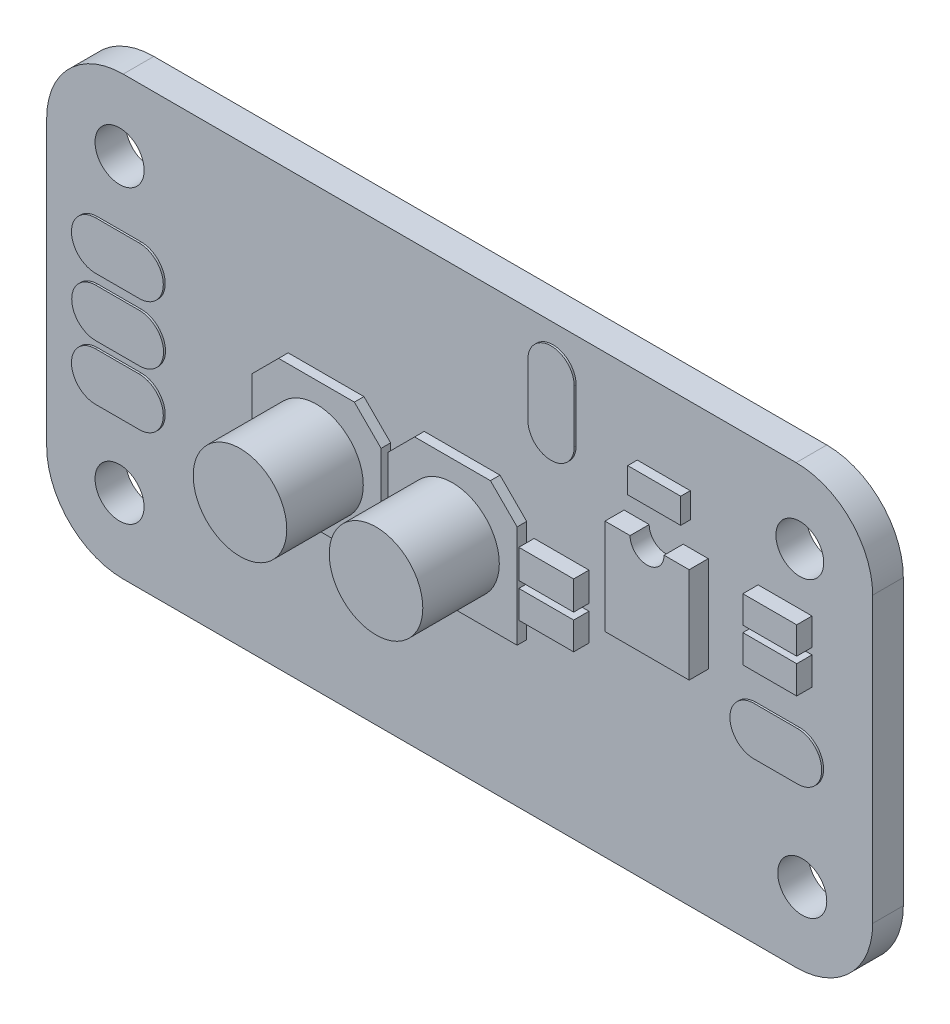
SolidWorks part; units mm, degrees
ref_plane "前视基准面" through (0, 0, 0) normal (0, 0, 1) x (1, 0, 0)
ref_plane "上视基准面" through (0, 0, 0) normal (0, 1, 0) x (1, 0, 0)
ref_plane "右视基准面" through (0, 0, 0) normal (1, 0, 0) x (0, 0, -1)
sketch "Model" plane through (0, 0, 0) normal (0, 0, 1) x (1, 0, 0)
  line L0 (38.097, 21.59) -> (2.5415, 21.59)
  line L1 (41.91, 2.543) -> (41.91, 17.9212)
  line L2 (2.54, -1.27) -> (38.2312, -1.27)
  line L3 (-1.2685, 17.7785) -> (-1.2685, 2.54)
  line L4 (22.225, 14.732) -> (26.67, 14.732)
  line L5 (26.67, 14.732) -> (27.051, 15.113)
  line L6 (27.051, 15.113) -> (27.94, 16.002)
  line L7 (27.94, 16.002) -> (27.94, 20.955)
  line L8 (22.225, 20.955) -> (22.225, 14.732)
  line L9 (22.225, 14.732) -> (23.876, 13.081)
  line L10 (23.876, 13.081) -> (23.876, 6.223)
  line L11 (23.876, 6.223) -> (25.019, 5.08)
  line L12 (25.019, 5.08) -> (39.624, 5.08)
  line L13 (39.624, 5.08) -> (41.021, 6.477)
  line L14 (41.021, 6.477) -> (41.021, 17.145)
  line L15 (28.956, 20.955) -> (22.225, 20.955)
  line L16 (37.211, 20.955) -> (28.956, 20.955)
  line L17 (33.8201, 11.811) -> (34.798, 11.811)
  line L18 (34.798, 11.811) -> (36.957, 9.652)
  line L19 (36.957, 9.652) -> (36.957, 8.509)
  line L20 (28.448, 11.811) -> (29.337, 11.811)
  line L21 (29.337, 11.811) -> (30.988, 10.16)
  line L22 (30.988, 10.16) -> (30.988, 8.509)
  line L23 (30.988, 8.509) -> (31.877, 7.62)
  line L24 (31.877, 7.62) -> (33.401, 7.62)
  line L25 (33.401, 7.62) -> (35.687, 5.334)
  line L26 (35.687, 5.334) -> (39.497, 5.334)
  line L27 (39.497, 5.334) -> (40.132, 5.969)
  line L28 (40.132, 5.969) -> (40.132, 9.398)
  line L29 (40.132, 9.398) -> (38.039, 11.491)
  line L30 (38.039, 11.491) -> (38.039, 12.573)
  line L31 (2.54, 13.208) -> (2.667, 13.208)
  line L32 (2.667, 13.208) -> (6.35, 16.891)
  line L33 (6.35, 16.891) -> (11.049, 16.891)
  line L34 (11.049, 16.891) -> (13.335, 14.605)
  line L35 (13.335, 14.605) -> (13.335, 13.335)
  line L36 (13.335, 7.236) -> (15.618, 7.236)
  line L37 (15.618, 7.236) -> (16.764, 8.382)
  line L38 (16.764, 8.382) -> (16.764, 10.922)
  line L39 (16.764, 10.922) -> (18.415, 12.573)
  line L40 (18.415, 12.573) -> (18.418, 12.576)
  line L41 (18.418, 12.576) -> (20.447, 12.576)
  line L42 (2.54, 7.112) -> (3.175, 7.112)
  line L43 (3.175, 7.112) -> (6.604, 3.683)
  line L44 (6.604, 3.683) -> (17.018, 3.683)
  line L45 (17.018, 3.683) -> (20.447, 7.112)
  line L46 (20.447, 7.112) -> (20.447, 7.236)
  line L47 (3.683, 10.16) -> (4.699, 10.16)
  line L48 (4.699, 10.16) -> (7.623, 7.236)
  line L49 (7.623, 7.236) -> (13.335, 7.236)
  line L50 (1.397, 10.16) -> (3.683, 10.16)
  line L51 (31.7414, 16.891) -> (31.7414, 12.7086)
  line L52 (31.7414, 12.7086) -> (32.639, 11.811)
  line L53 (32.639, 11.811) -> (33.8201, 11.811)
  line L54 (28.4099, 13.081) -> (29.464, 13.081)
  line L55 (29.464, 13.081) -> (30.2346, 13.8516)
  line L56 (30.2346, 13.8516) -> (30.2346, 16.891)
  line L57 (20.447, 12.576) -> (21.46, 12.576)
  line L58 (21.46, 12.576) -> (23.495, 10.541)
  line L59 (23.495, 10.541) -> (24.954, 10.541)
  line L60 (24.954, 8.763) -> (24.954, 10.541)
  line L61 (26.354, 8.763) -> (26.354, 10.541)
  line L62 (26.354, 10.541) -> (28.4099, 10.541)
  line L63 (20.447, 7.236) -> (22.736, 7.236)
  line L64 (22.736, 7.236) -> (23.495, 6.477)
  line L65 (23.495, 6.477) -> (25.527, 6.477)
  line L66 (25.527, 6.477) -> (26.354, 7.304)
  line L67 (26.354, 7.304) -> (26.354, 8.763)
  line L68 (36.638, 14.351) -> (36.576, 14.289)
  line L69 (36.576, 14.289) -> (36.576, 12.573)
  line L70 (38.038, 14.351) -> (38.038, 12.573)
  line L71 (24.954, 10.541) -> (24.954, 11.238)
  line L72 (24.954, 11.238) -> (25.527, 11.811)
  line L73 (25.527, 11.811) -> (28.448, 11.811)
  line L74 (33.8201, 13.081) -> (35.052, 13.081)
  line L75 (35.052, 13.081) -> (35.56, 12.573)
  line L76 (35.56, 12.573) -> (36.576, 12.573)
  line L77 (25.273, 18.288) -> (25.273, 14.859)
  line L78 (25.273, 14.859) -> (27.051, 13.081)
  line L79 (27.051, 13.081) -> (28.4099, 13.081)
  line L80 (13.335, 13.335) -> (13.335, 8.89)
  line L81 (13.335, 8.89) -> (14.605, 7.62)
  line L82 (14.605, 7.62) -> (33.401, 7.62)
  line L83 (33.401, 7.62) -> (35.433, 5.588)
  line L84 (35.433, 5.588) -> (38.862, 5.588)
  line L85 (38.862, 5.588) -> (39.624, 6.35)
  line L86 (39.624, 6.35) -> (39.624, 9.779)
  line L87 (39.624, 9.779) -> (38.354, 11.049)
  line L88 (38.354, 11.049) -> (37.084, 11.049)
  line L89 (37.084, 11.049) -> (36.576, 11.557)
  line L90 (36.576, 11.557) -> (36.576, 12.573)
  line L91 (12.5957, 6.5504) -> (9.9593, 6.5303)
  line L92 (9.9593, 6.5303) -> (9.9593, 11.8872)
  line L93 (9.9593, 11.8872) -> (11.3538, 13.2817)
  line L94 (11.3538, 13.2817) -> (12.6492, 13.2683)
  line L95 (14.0427, 6.5365) -> (16.7112, 6.5298)
  line L96 (16.7112, 6.5298) -> (16.7112, 11.886)
  line L97 (16.7112, 11.886) -> (15.315, 13.2822)
  line L98 (15.315, 13.2822) -> (14.0208, 13.2822)
  line L99 (19.7077, 6.5504) -> (17.0713, 6.5303)
  line L100 (17.0713, 6.5303) -> (17.0713, 11.8872)
  line L101 (17.0713, 11.8872) -> (18.4658, 13.2817)
  line L102 (18.4658, 13.2817) -> (19.7612, 13.2683)
  line L103 (21.1547, 6.5365) -> (23.8232, 6.5298)
  line L104 (23.8232, 6.5298) -> (23.8232, 11.886)
  line L105 (23.8232, 11.886) -> (22.427, 13.2822)
  line L106 (22.427, 13.2822) -> (21.1328, 13.2822)
  line L107 (24.264, 10.1412) -> (24.264, 10.9413)
  line L108 (25.3737, 9.8314) -> (24.5738, 9.8314)
  line L109 (25.3737, 11.251) -> (24.5738, 11.251)
  line L110 (25.9496, 9.8256) -> (26.7496, 9.8256)
  line L111 (27.0595, 10.1354) -> (27.0595, 10.9354)
  line L112 (25.9496, 11.2452) -> (26.7496, 11.2452)
  line L113 (35.948, 12.1732) -> (35.948, 12.9733)
  line L114 (37.0577, 11.8634) -> (36.2578, 11.8634)
  line L115 (37.0577, 13.283) -> (36.2578, 13.283)
  line L116 (37.6336, 11.8576) -> (38.4336, 11.8576)
  line L117 (38.7435, 12.1674) -> (38.7435, 12.9674)
  line L118 (37.6336, 13.2772) -> (38.4336, 13.2772)
  line L119 (24.264, 8.3632) -> (24.264, 9.1633)
  line L120 (25.3737, 8.0534) -> (24.5738, 8.0534)
  line L121 (25.3737, 9.473) -> (24.5738, 9.473)
  line L122 (25.9496, 8.0476) -> (26.7496, 8.0476)
  line L123 (27.0595, 8.3574) -> (27.0595, 9.1574)
  line L124 (25.9496, 9.4672) -> (26.7496, 9.4672)
  line L125 (35.948, 13.9512) -> (35.948, 14.7513)
  line L126 (37.0577, 13.6414) -> (36.2578, 13.6414)
  line L127 (37.0577, 15.061) -> (36.2578, 15.061)
  line L128 (37.6336, 13.6356) -> (38.4336, 13.6356)
  line L129 (38.7435, 13.9454) -> (38.7435, 14.7454)
  line L130 (37.6336, 15.0552) -> (38.4336, 15.0552)
  line L131 (31.4142, 16.2304) -> (32.3731, 16.2304)
  line L132 (32.3731, 16.2304) -> (32.3731, 17.5516)
  line L133 (32.3731, 17.5516) -> (31.4142, 17.5516)
  line L134 (30.5618, 16.2304) -> (29.6029, 16.2304)
  line L135 (29.6029, 16.2304) -> (29.6029, 17.5516)
  line L136 (29.6029, 17.5516) -> (30.5618, 17.5516)
  line L137 (28.915, 14.946) -> (30.226, 14.946)
  line L138 (33.315, 14.946) -> (32.004, 14.946)
  line L139 (28.915, 14.8663) -> (28.915, 14.946)
  line L140 (28.915, 13.5963) -> (28.915, 13.8357)
  line L141 (28.915, 12.3263) -> (28.915, 12.5657)
  line L142 (28.915, 11.0563) -> (28.915, 11.2957)
  line L143 (28.915, 9.946) -> (28.915, 10.0257)
  line L144 (33.315, 14.8663) -> (33.315, 14.946)
  line L145 (33.315, 13.5963) -> (33.315, 13.8357)
  line L146 (33.315, 12.3263) -> (33.315, 12.5657)
  line L147 (33.315, 11.0563) -> (33.315, 11.2957)
  line L148 (33.315, 9.946) -> (33.315, 10.0257)
  line L149 (33.315, 9.946) -> (28.915, 9.946)
  line L150 (23.876, 17.399) -> (23.876, 19.5262) construction
  arc A0 (2.5415, 21.5885) -> (-1.2685, 17.7785) centre (2.5415, 17.7785) ccw
  arc A1 (-1.27, 2.54) -> (2.54, -1.27) centre (2.54, 2.54) ccw
  arc A2 (38.1, -1.267) -> (41.91, 2.543) centre (38.1, 2.543) ccw
  arc A3 (41.907, 17.78) -> (38.097, 21.59) centre (38.097, 17.78) ccw
  arc A4 (41.021, 17.145) -> (37.211, 20.955) centre (37.211, 17.145) ccw
  arc A5 (26.7497, 9.8256) -> (27.0595, 10.1354) centre (26.7497, 10.1354) ccw
  arc A6 (27.0595, 10.9354) -> (26.7497, 11.2452) centre (26.7497, 10.9354) ccw
  arc A7 (24.264, 10.1412) -> (24.5738, 9.8314) centre (24.5738, 10.1412) ccw
  arc A8 (24.5738, 11.251) -> (24.264, 10.9412) centre (24.5738, 10.9412) ccw
  arc A9 (38.4337, 11.8576) -> (38.7435, 12.1674) centre (38.4337, 12.1674) ccw
  arc A10 (38.7435, 12.9674) -> (38.4337, 13.2772) centre (38.4337, 12.9674) ccw
  arc A11 (35.948, 12.1732) -> (36.2578, 11.8634) centre (36.2578, 12.1732) ccw
  arc A12 (36.2578, 13.283) -> (35.948, 12.9732) centre (36.2578, 12.9732) ccw
  arc A13 (26.7497, 8.0476) -> (27.0595, 8.3574) centre (26.7497, 8.3574) ccw
  arc A14 (27.0595, 9.1574) -> (26.7497, 9.4672) centre (26.7497, 9.1574) ccw
  arc A15 (24.264, 8.3632) -> (24.5738, 8.0534) centre (24.5738, 8.3632) ccw
  arc A16 (24.5738, 9.473) -> (24.264, 9.1632) centre (24.5738, 9.1632) ccw
  arc A17 (38.4337, 13.6356) -> (38.7435, 13.9454) centre (38.4337, 13.9454) ccw
  arc A18 (38.7435, 14.7454) -> (38.4337, 15.0552) centre (38.4337, 14.7454) ccw
  arc A19 (35.948, 13.9512) -> (36.2578, 13.6414) centre (36.2578, 13.9512) ccw
  arc A20 (36.2578, 15.061) -> (35.948, 14.7512) centre (36.2578, 14.7512) ccw
  arc A21 (30.226, 14.946) -> (32.004, 14.9454) centre (31.115, 14.9457) ccw
  circle A22 centre (27.715, 14.351) radius 0.1501
  circle A23 centre (29.845, 14.351) radius 0.1501
  circle A24 centre (28.4099, 15.0876) radius 0.1501
  circle A25 centre (2.54, 17.78) radius 1.2818
  circle A26 centre (2.54, 17.78) radius 2.0508
  circle A27 centre (2.54, 17.78) radius 1.2818
  circle A28 centre (2.54, 17.78) radius 2.0508
  circle A29 centre (2.54, 17.78) radius 1.25
  circle A30 centre (2.54, 17.78) radius 2
  circle A31 centre (2.54, 2.54) radius 1.2818
  circle A32 centre (2.54, 2.54) radius 2.0508
  circle A33 centre (2.54, 2.54) radius 1.2818
  circle A34 centre (2.54, 2.54) radius 2.0508
  circle A35 centre (2.54, 2.54) radius 1.25
  circle A36 centre (2.54, 2.54) radius 2
  circle A37 centre (38.227, 2.54) radius 1.2818
  circle A38 centre (38.227, 2.54) radius 2.0508
  circle A39 centre (38.227, 2.54) radius 1.2818
  circle A40 centre (38.227, 2.54) radius 2.0508
  circle A41 centre (38.227, 2.54) radius 1.25
  circle A42 centre (38.227, 2.54) radius 2
  circle A43 centre (38.1, 17.78) radius 1.2818
  circle A44 centre (38.1, 17.78) radius 2.0508
  circle A45 centre (38.1, 17.78) radius 1.2818
  circle A46 centre (38.1, 17.78) radius 2.0508
  circle A47 centre (38.1, 17.78) radius 1.25
  circle A48 centre (38.1, 17.78) radius 2
  circle A49 centre (13.335, 13.335) radius 0.381
  circle A50 centre (13.335, 13.335) radius 0.1905
  circle A51 centre (13.335, 11.557) radius 0.381
  circle A52 centre (13.335, 11.557) radius 0.1905
  circle A53 centre (13.335, 12.446) radius 0.381
  circle A54 centre (13.335, 12.446) radius 0.1905
  circle A55 centre (36.576, 12.573) radius 0.3048
  circle A56 centre (36.576, 12.573) radius 0.1524
  circle A57 centre (20.447, 13.335) radius 0.3048
  circle A58 centre (20.447, 13.335) radius 0.1524
  circle A59 centre (28.448, 11.811) radius 0.3048
  circle A60 centre (28.448, 11.811) radius 0.1524
  circle A61 centre (24.7, 10.541) radius 0.3048
  circle A62 centre (24.7, 10.541) radius 0.1524
  circle A63 centre (24.7, 8.763) radius 0.3048
  circle A64 centre (24.7, 8.763) radius 0.1524
  circle A65 centre (29.972, 9.398) radius 0.3048
  circle A66 centre (29.972, 9.398) radius 0.1524
  circle A67 centre (38.038, 12.573) radius 0.3048
  circle A68 centre (38.038, 12.573) radius 0.1524
  circle A69 centre (38.038, 14.351) radius 0.3048
  circle A70 centre (38.038, 14.351) radius 0.1524
  circle A71 centre (2.159, 10.16) radius 0.3048
  circle A72 centre (2.159, 10.16) radius 0.1524
  circle A73 centre (1.397, 10.16) radius 0.3048
  circle A74 centre (1.397, 10.16) radius 0.1524
  circle A75 centre (2.921, 10.16) radius 0.3048
  circle A76 centre (2.921, 10.16) radius 0.1524
  circle A77 centre (3.683, 10.16) radius 0.3048
  circle A78 centre (3.683, 10.16) radius 0.1524
  circle A79 centre (20.447, 11.811) radius 0.3048
  circle A80 centre (20.447, 11.811) radius 0.1524
  circle A81 centre (20.447, 12.576) radius 0.3048
  circle A82 centre (20.447, 12.576) radius 0.1524
  text T0 "+15V" font "ARIAL" height 1.016
  text T1 "-15V" font "ARIAL" height 1.016
  text T2 "GND" font "ARIAL" height 1.016
  text T3 "TIP" font "ARIAL" height 1.016
  text T4 "OUT" font "ARIAL" height 1.016
  text T5 "Tunneling Current Amplifier" font "ARIAL" height 1.016
  text T6 "C1" font "ARIAL" height 0.762
  text T7 "C2" font "ARIAL" height 0.762
  text T8 "C3" font "ARIAL" height 0.762
  text T9 "C4" font "ARIAL" height 0.762
  text T10 "C5" font "ARIAL" height 0.762
  text T11 "C6" font "ARIAL" height 0.762
  text T12 "R1" font "ARIAL" height 0.762
  text T13 "U1" font "ARIAL" height 0.762
sketch "草图2" plane through (0, 0, 0) normal (0, 0, 1) x (1, 0, 0)
  line L29 (38.097, 21.59) -> (2.5415, 21.59) construction
  line L30 (-1.2685, 21.59) -> (41.91, 21.59)
  line L31 (-1.2685, 21.59) -> (-1.2685, -1.27)
  line L32 (-1.2685, -1.27) -> (41.91, -1.27)
  line L33 (41.91, 21.59) -> (41.91, -1.27)
  line L34 (2.54, -1.27) -> (38.2312, -1.27) construction
  line L35 (-1.2685, 17.7785) -> (-1.2685, 2.54) construction
  line L36 (41.91, 2.543) -> (41.91, 17.9212) construction
extrude "凸台-拉伸1" add sketch "草图2" along normal blind 1.6
sketch "草图3" plane through (0, 0, 1.6) normal (0, 0, 1) x (1, 0, 0)
  circle A0 centre (2.5415, 17.7785) radius 1.2839
  circle A1 centre (2.54, 2.54) radius 1.2818
  circle A2 centre (38.227, 2.54) radius 1.2818
  circle A3 centre (38.1, 17.78) radius 1.25
extrude "切除-拉伸1" cut sketch "草图3" against normal blind 1.6
sketch "草图4" plane through (0, 0, 1.6) normal (0, 0, 1) x (1, 0, 0)
  line L0 (32.004, 14.946) -> (33.315, 14.946)
  line L1 (28.915, 14.946) -> (30.226, 14.946)
  line L2 (28.915, 14.946) -> (28.915, 9.946)
  line L3 (28.915, 9.946) -> (33.315, 9.946)
  line L4 (33.315, 14.946) -> (33.315, 9.946)
  arc A0 (30.226, 14.946) -> (32.004, 14.946) centre (31.115, 14.9457) ccw
extrude "凸台-拉伸2" add sketch "草图4" along normal blind 1
sketch "草图5" plane through (0, 0, 1.6) normal (0, 0, 1) x (1, 0, 0)
  line L0 (11.3538, 13.2817) -> (9.9593, 11.8872)
  line L1 (9.9593, 11.8872) -> (9.9593, 6.5303)
  line L2 (9.9593, 6.5303) -> (16.7112, 6.5298)
  line L3 (16.7112, 6.5298) -> (16.7112, 11.886)
  line L4 (16.7112, 11.886) -> (15.315, 13.2822)
  line L5 (15.315, 13.2822) -> (11.3538, 13.2817)
  line L6 (18.4658, 13.2817) -> (17.0713, 11.8872)
  line L7 (17.0713, 11.8872) -> (17.0713, 6.5303)
  line L8 (17.0713, 6.5303) -> (23.8232, 6.5298)
  line L9 (23.8232, 6.5298) -> (23.8232, 11.886)
  line L10 (23.8232, 11.886) -> (22.427, 13.2822)
  line L11 (22.427, 13.2822) -> (18.4658, 13.2817)
extrude "凸台-拉伸3" add sketch "草图5" along normal blind 0.5
sketch "草图6" plane through (0, 0, 2.1) normal (0, 0, 1) x (1, 0, 0)
  line L0 (13.335, 13.335) -> (13.335, 8.89) construction
  circle A0 centre (13.335, 9.752) radius 2.4458
  circle A1 centre (20.4464, 9.752) radius 2.4458
extrude "凸台-拉伸4" add sketch "草图6" along normal blind 4
sketch "草图7" plane through (0, 0, 1.6) normal (0, 0, 1) x (1, 0, 0)
  line L0 (1.397, 10.16) -> (3.683, 10.16) construction
  line L1 (1.397, 11.4173) -> (3.683, 11.4173)
  line L2 (1.397, 8.9027) -> (3.683, 8.9027)
  line L3 (1.3841, 13.2061) -> (3.6701, 13.2061) construction
  line L4 (1.3841, 14.4633) -> (3.6701, 14.4633)
  line L5 (1.3841, 11.9488) -> (3.6701, 11.9488)
  line L6 (1.3841, 7.2731) -> (3.6701, 7.2731) construction
  line L7 (1.3841, 8.5303) -> (3.6701, 8.5303)
  line L8 (1.3841, 6.0158) -> (3.6701, 6.0158)
  line L9 (35.8016, 8.4315) -> (38.0876, 8.4315) construction
  line L14 (35.8016, 9.6888) -> (38.0876, 9.6888)
  line L15 (35.8016, 7.1743) -> (38.0876, 7.1743)
  line L16 (25.1973, 19.3594) -> (25.1973, 16.5963) construction
  line L17 (26.4083, 19.3594) -> (26.4083, 16.5963)
  line L18 (23.9863, 19.3594) -> (23.9863, 16.5963)
  arc A0 (1.397, 11.4173) -> (1.397, 8.9027) centre (1.397, 10.16) ccw
  arc A1 (3.683, 8.9027) -> (3.683, 11.4173) centre (3.683, 10.16) ccw
  arc A2 (1.3841, 14.4633) -> (1.3841, 11.9488) centre (1.3841, 13.2061) ccw
  arc A3 (3.6701, 11.9488) -> (3.6701, 14.4633) centre (3.6701, 13.2061) ccw
  arc A4 (1.3841, 8.5303) -> (1.3841, 6.0158) centre (1.3841, 7.2731) ccw
  arc A5 (3.6701, 6.0158) -> (3.6701, 8.5303) centre (3.6701, 7.2731) ccw
  arc A10 (35.8016, 9.6888) -> (35.8016, 7.1743) centre (35.8016, 8.4315) ccw
  arc A11 (38.0876, 7.1743) -> (38.0876, 9.6888) centre (38.0876, 8.4315) ccw
  arc A12 (26.4083, 19.3594) -> (23.9863, 19.3594) centre (25.1973, 19.3594) ccw
  arc A13 (23.9863, 16.5963) -> (26.4083, 16.5963) centre (25.1973, 16.5963) ccw
  point P4 (2.54, 10.16)
  point P11 (2.5271, 13.2061)
  point P18 (2.5271, 7.2731)
  point P25 (36.9446, 8.4315)
  point P32 (25.1973, 17.9779)
extrude "凸台-拉伸5" add sketch "草图7" along normal blind 0.1
sketch "草图9" plane through (0, 0, 1.6) normal (0, 0, 1) x (1, 0, 0)
  line L1 (35.921, 15.061) -> (38.7368, 15.061)
  line L2 (35.921, 15.061) -> (35.921, 13.639)
  line L3 (35.921, 13.639) -> (38.7368, 13.639)
  line L4 (38.7368, 15.061) -> (38.7368, 13.639)
  line L5 (35.921, 13.3007) -> (38.7368, 13.3007)
  line L6 (35.921, 13.3007) -> (35.921, 11.838)
  line L7 (35.921, 11.838) -> (38.7368, 11.838)
  line L8 (38.7368, 13.3007) -> (38.7368, 11.838)
  line L9 (24.2121, 11.3087) -> (27.0778, 11.3087)
  line L10 (24.2121, 11.3087) -> (24.2121, 9.8029)
  line L11 (24.2121, 9.8029) -> (27.0778, 9.8029)
  line L12 (27.0778, 11.3087) -> (27.0778, 9.8029)
  line L13 (24.2121, 9.4467) -> (27.0778, 9.4467)
  line L14 (24.2121, 9.4467) -> (24.2121, 8.0058)
  line L15 (24.2121, 8.0058) -> (27.0778, 8.0058)
  line L16 (27.0778, 9.4467) -> (27.0778, 8.0058)
extrude "凸台-拉伸6" add sketch "草图9" along normal blind 0.8
sketch "草图10" plane through (0, 0, 1.6) normal (0, 0, 1) x (1, 0, 0)
  line L1 (29.6029, 17.5516) -> (32.3731, 17.5516)
  line L2 (29.6029, 17.5516) -> (29.6029, 16.2304)
  line L3 (29.6029, 16.2304) -> (32.3731, 16.2304)
  line L4 (32.3731, 17.5516) -> (32.3731, 16.2304)
extrude "凸台-拉伸7" add sketch "草图10" along normal blind 0.5
fillet "圆角1" radius 4 4 edges at (41.91, 21.59, 0.8) (41.91, -1.27, 0.8) (-1.2685, -1.27, 0.8) (-1.2685, 21.59, 0.8)
